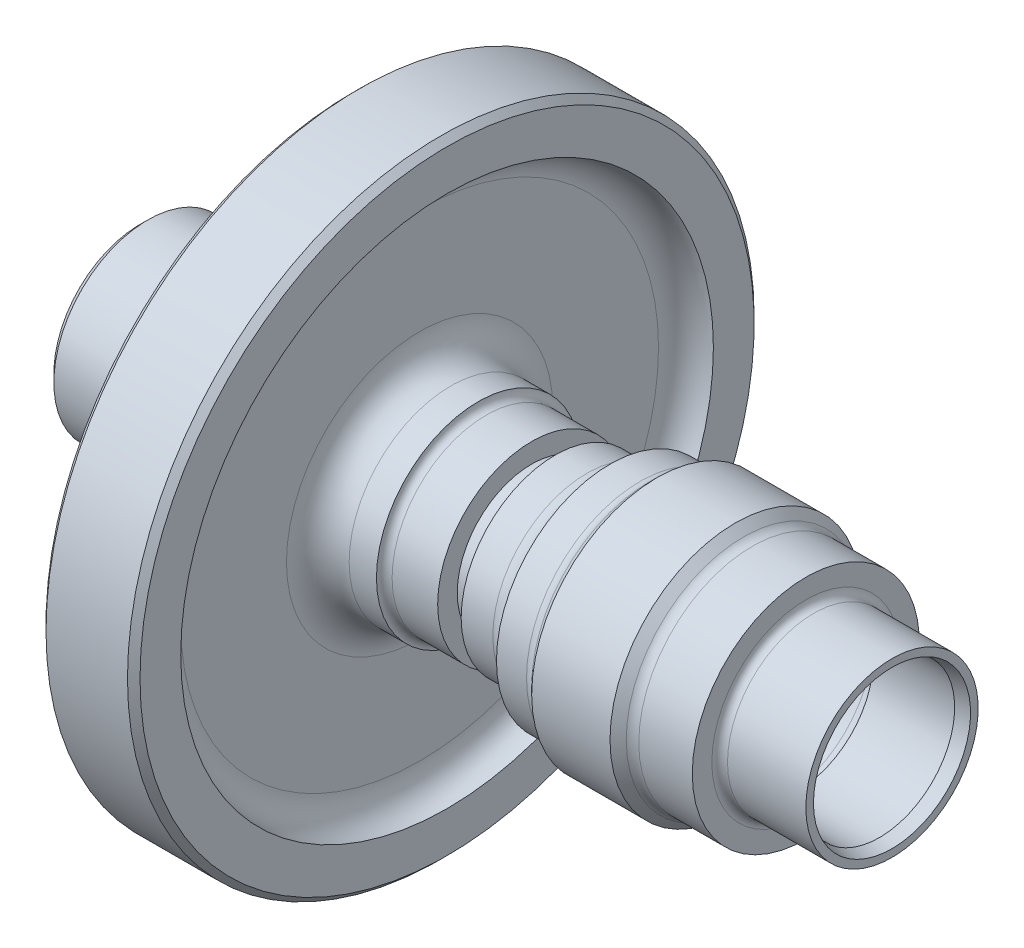
SolidWorks part; units mm, degrees
ref_plane "Front Plane" through (0, 0, 0) normal (0, 0, 1) x (1, 0, 0)
ref_plane "Top Plane" through (0, 0, 0) normal (0, 1, 0) x (1, 0, 0)
ref_plane "Right Plane" through (0, 0, 0) normal (1, 0, 0) x (0, 0, -1)
sketch "Sketch1" plane through (0, 0, 0) normal (0, 0, 1) x (1, 0, 0)
  line L0 (0, 0) -> (142.8155, 0) construction
  line L1 (0, 15.0812) -> (0, 17.4625)
  line L2 (0, 17.4625) -> (1.5875, 19.05)
  line L3 (1.5875, 19.05) -> (16.1925, 19.05)
  line L4 (17.78, 20.6375) -> (17.78, 25.4)
  line L5 (17.78, 25.4) -> (21.2785, 25.4)
  line L6 (26.041, 20.6375) -> (42.3926, 20.6375)
  line L7 (48.7426, 26.9875) -> (48.7426, 48.4124)
  line L8 (43.18, 53.975) -> (43.18, 62.23)
  line L9 (44.45, 63.5) -> (60.96, 63.5)
  line L10 (62.23, 62.23) -> (62.23, 53.975)
  line L11 (56.6674, 48.4124) -> (56.6674, 26.9875)
  line L12 (63.0174, 20.6375) -> (68.5536, 20.6375)
  line L13 (70.1411, 19.05) -> (79.375, 19.05)
  line L14 (79.375, 19.05) -> (79.375, 15.0812)
  line L15 (79.375, 15.0812) -> (84.1375, 15.0812)
  line L16 (84.1375, 15.0812) -> (84.1375, 19.05)
  line L17 (84.1375, 19.05) -> (90.5552, 19.05)
  line L18 (95.25, 23.0124) -> (101.3353, 23.0124)
  line L19 (103.1313, 23.7563) -> (104.775, 25.4)
  line L20 (104.775, 25.4) -> (120.65, 25.4)
  line L21 (120.65, 25.4) -> (122.2937, 23.7563)
  line L22 (124.0897, 23.0124) -> (134.9375, 23.0124)
  line L23 (134.9375, 23.0124) -> (134.9375, 19.05)
  line L24 (136.525, 17.4625) -> (152.4, 17.4625)
  line L25 (152.4, 17.4625) -> (152.4, 15.9206)
  line L26 (149.86, 15.24) -> (133.35, 15.24)
  line L27 (129.54, 19.05) -> (106.68, 19.05)
  line L28 (101.6, 13.97) -> (101.6, 11.9062)
  line L29 (101.6, 11.9062) -> (26.67, 11.9062)
  line L30 (25.4, 13.1762) -> (25.4, 15.0813)
  line L31 (23.8188, 16.6624) -> (14.1675, 16.6624)
  line L32 (26.67, 11.9062) -> (25.4, 13.1762)
  line L33 (11.1125, 16.0569) -> (11.1125, 15.875)
  line L34 (149.86, 15.24) -> (152.4, 15.9206)
  line L35 (60.96, 63.5) -> (62.23, 62.23)
  line L36 (43.18, 62.23) -> (44.45, 63.5)
  line L38 (11.1125, 15.875) -> (2.9623, 15.875)
  line L39 (1.5875, 15.0812) -> (0, 15.0812)
  arc A0 (16.1925, 19.05) -> (17.78, 20.6375) centre (16.1925, 20.6375) ccw
  arc A1 (21.2785, 25.4) -> (26.041, 20.6375) centre (26.041, 25.4) ccw
  arc A2 (42.3926, 20.6375) -> (48.7426, 26.9875) centre (42.3926, 26.9875) ccw
  arc A3 (48.7426, 48.4124) -> (43.18, 53.975) centre (43.18, 48.4124) ccw
  arc A4 (62.23, 53.975) -> (56.6674, 48.4124) centre (62.23, 48.4124) ccw
  arc A5 (56.6674, 26.9875) -> (63.0174, 20.6375) centre (63.0174, 26.9875) ccw
  arc A6 (68.5536, 20.6375) -> (70.1411, 19.05) centre (70.1411, 20.6375) ccw
  arc A7 (90.5552, 19.05) -> (95.25, 23.0124) centre (90.5552, 23.8125) ccw
  arc A8 (134.9375, 19.05) -> (136.525, 17.4625) centre (136.525, 19.05) ccw
  arc A9 (133.35, 15.24) -> (129.54, 19.05) centre (129.54, 15.24) ccw
  arc A10 (106.68, 19.05) -> (101.6, 13.97) centre (106.68, 13.97) ccw
  arc A11 (25.4, 15.0813) -> (23.8188, 16.6624) centre (23.8188, 15.0813) ccw
  arc A12 (2.9623, 15.875) -> (1.5875, 15.0812) centre (2.9623, 14.2875) ccw
  arc A13 (14.1675, 16.6624) -> (11.1125, 16.0569) centre (12.7, 16.0569) ccw
  arc A14 (101.3353, 23.0124) -> (103.1313, 23.7563) centre (101.3353, 25.5524) ccw
  arc A15 (124.0897, 23.0124) -> (122.2937, 23.7563) centre (124.0897, 25.5524) cw
  point P19 (62.23, 63.5)
  point P20 (43.18, 63.5)
  point P53 (25.4, 11.9062)
  dimension "D1" = 1.5875
  dimension "D2" = 17.6444
  dimension "D6" = 1.5875
  dimension "D12" = 12.7
  dimension "D18" = 3.81
  dimension "D21" = 5.08
  dimension "D25" = 4.7625
  dimension "D29" = 1.5875
  dimension "D30" = 3.4985
  dimension "D31" = 6.35
  dimension "D32" = 6.35
  dimension "D33" = 5.5626
  dimension "D34" = 34.925
  dimension "D38" = 107.95
  dimension "D44" = 2.54
  dimension "D45" = 2.54
  dimension "D48" = 1.5875
  dimension "D3" = 38.1
  dimension "D4" = 45
  dimension "D5" = 1.5875
  dimension "D7" = 1.5875
  dimension "D8" = 30.1625
  dimension "D9" = 31.75
  dimension "D10" = 33.3248
  dimension "D11" = 25.4
  dimension "D13" = 23.8125
  dimension "D14" = 152.4
  dimension "D16" = 17.4625
  dimension "D17" = 19.05
  dimension "D19" = 38.1
  dimension "D20" = 50.8
  dimension "D22" = 31.75
  dimension "D23" = 15.875
  dimension "D24" = 46.0248
  dimension "D26" = 9.525
  dimension "D27" = 50.8
  dimension "D28" = 17.78
  dimension "D35" = 19.05
  dimension "D36" = 7.9248
  dimension "D37" = 25.4
  dimension "D39" = 30.1625
  dimension "D40" = 127
  dimension "D41" = 4.7625
  dimension "D46" = 38.1
  dimension "D47" = 50.8
  dimension "D49" = 15
  dimension "D50" = 2.54
sketch "Sketch2" plane through (0, 0, 0) normal (0, 0, 1) x (1, 0, 0)
  line L0 (-19.9256, 0) -> (168.6458, 0) construction
  line L1 (-6.35, 69.85) -> (158.75, 69.85)
  line L2 (-6.35, 69.85) -> (-6.35, 0)
  line L3 (-6.35, 0) -> (158.75, 0)
  line L4 (158.75, 69.85) -> (158.75, 0)
  line L5 (0, 15.0812) -> (0, 17.4625) construction
  line L6 (152.4, 17.4625) -> (152.4, 15.9206) construction
  dimension "D1" = 139.7
  dimension "D2" = 6.35
  dimension "D3" = 6.35
revolve "Stock" add sketch "Sketch2" angle 360 about L0
sketch "Sketch3" plane through (0, 0, 0) normal (0, 0, 1) x (1, 0, 0)
  line L0 (67.1974, 66.0709) -> (153.302, 66.0709)
  line L1 (154.572, 64.8009) -> (154.572, 0)
  line L2 (158.75, -69.85) -> (158.75, 69.85) construction
  line L3 (158.75, 69.85) -> (-6.35, 69.85) construction
  line L4 (158.75, 0) -> (158.75, 69.85)
  line L5 (158.75, 69.85) -> (66.3084, 69.85)
  line L6 (66.3084, 66.9599) -> (66.3084, 69.85)
  line L7 (154.572, 0) -> (158.75, 0)
  line L8 (-15.1072, 0) -> (164.7172, 0) construction
  line L9 (153.302, 66.0709) -> (154.572, 64.8009)
  arc A0 (67.1974, 66.0709) -> (66.3084, 66.9599) centre (67.1974, 66.9599) cw
  point P1 (154.572, 66.0709)
  dimension "D1" = 0.889
revolve "Cut-Revolve1" cut sketch "Sketch3" angle 360 about L8
sketch "Sketch4" plane through (0, 0, 0) normal (0, 0, 1) x (1, 0, 0)
  line L0 (44.45, 63.5) -> (60.96, 63.5) construction
  line L1 (43.18, 62.23) -> (44.45, 63.5) construction
  line L2 (43.18, 53.975) -> (43.18, 62.23) construction
  line L3 (48.7426, 26.9875) -> (48.7426, 48.4124) construction
  line L4 (26.041, 20.6375) -> (42.3926, 20.6375) construction
  line L5 (17.78, 25.4) -> (21.2785, 25.4) construction
  line L6 (17.78, 20.6375) -> (17.78, 25.4) construction
  line L7 (1.5875, 19.05) -> (16.1925, 19.05) construction
  line L8 (0, 17.4625) -> (1.5875, 19.05) construction
  line L9 (0, 15.0812) -> (0, 17.4625) construction
  line L10 (1.5875, 15.0812) -> (0, 15.0812) construction
  line L11 (11.1125, 15.875) -> (2.9623, 15.875) construction
  line L12 (23.8188, 16.6624) -> (14.1675, 16.6624) construction
  line L13 (25.4, 13.1762) -> (25.4, 15.0813) construction
  line L14 (26.67, 11.9062) -> (25.4, 13.1762) construction
  line L15 (101.6, 11.9062) -> (26.67, 11.9062) construction
  line L16 (44.45, 63.5) -> (69.5582, 63.5)
  line L17 (43.18, 62.23) -> (44.45, 63.5)
  line L18 (43.18, 53.975) -> (43.18, 62.23)
  line L19 (48.7426, 26.9875) -> (48.7426, 48.4124)
  line L20 (26.041, 20.6375) -> (42.3926, 20.6375)
  line L21 (17.78, 25.4) -> (21.2785, 25.4)
  line L22 (17.78, 20.6375) -> (17.78, 25.4)
  line L23 (1.5875, 19.05) -> (16.1925, 19.05)
  line L24 (0, 17.4625) -> (1.5875, 19.05)
  line L25 (0, 15.0812) -> (0, 17.4625)
  line L26 (1.5875, 15.0812) -> (0, 15.0812)
  line L27 (11.1125, 15.875) -> (2.9623, 15.875)
  line L28 (23.8188, 16.6624) -> (14.1675, 16.6624)
  line L29 (25.4, 13.1762) -> (25.4, 15.0813)
  line L30 (26.67, 11.9062) -> (25.4, 13.1762)
  line L31 (107.95, 11.9063) -> (26.67, 11.9062)
  line L32 (70.4472, 66.0709) -> (70.4472, 64.389)
  line L33 (153.302, 66.0709) -> (67.1974, 66.0709) construction
  line L34 (107.95, 11.9063) -> (115.104, 0)
  line L35 (0, 0) -> (142.8155, 0) construction
  line L36 (-6.35, 69.85) -> (-6.35, -69.85) construction
  line L38 (66.3084, 69.85) -> (-6.35, 69.85) construction
  line L39 (-6.35, 69.85) -> (-6.35, 0)
  line L40 (11.1125, 15.875) -> (11.1125, 16.0569)
  line L41 (66.3084, 69.85) -> (-6.35, 69.85)
  line L42 (70.4472, 66.0709) -> (67.1974, 66.0709)
  line L43 (171.8406, 0) -> (-23.4157, 0) construction
  line L44 (66.3084, 66.9599) -> (66.3084, 69.85)
  line L45 (154.572, -64.8009) -> (154.572, 64.8009) construction
  line L46 (-6.35, 0) -> (115.104, 0)
  arc A0 (48.7426, 48.4124) -> (43.18, 53.975) centre (43.18, 48.4124) ccw construction
  arc A1 (42.3926, 20.6375) -> (48.7426, 26.9875) centre (42.3926, 26.9875) ccw construction
  arc A2 (21.2785, 25.4) -> (26.041, 20.6375) centre (26.041, 25.4) ccw construction
  arc A3 (16.1925, 19.05) -> (17.78, 20.6375) centre (16.1925, 20.6375) ccw construction
  arc A4 (2.9623, 15.875) -> (1.5875, 15.0812) centre (2.9623, 14.2875) ccw construction
  arc A5 (14.1675, 16.6624) -> (11.1125, 16.0569) centre (12.7, 16.0569) ccw construction
  arc A6 (25.4, 15.0813) -> (23.8188, 16.6624) centre (23.8188, 15.0813) ccw construction
  arc A7 (48.7426, 48.4124) -> (43.18, 53.975) centre (43.18, 48.4124) ccw
  arc A8 (42.3926, 20.6375) -> (48.7426, 26.9875) centre (42.3926, 26.9875) ccw
  arc A9 (21.2785, 25.4) -> (26.041, 20.6375) centre (26.041, 25.4) ccw
  arc A10 (16.1925, 19.05) -> (17.78, 20.6375) centre (16.1925, 20.6375) ccw
  arc A11 (2.9623, 15.875) -> (1.5875, 15.0812) centre (2.9623, 14.2875) ccw
  arc A12 (14.1675, 16.6624) -> (11.1125, 16.0569) centre (12.7, 16.0569) ccw
  arc A13 (25.4, 15.0813) -> (23.8188, 16.6624) centre (23.8188, 15.0813) ccw
  arc A14 (69.5582, 63.5) -> (70.4472, 64.389) centre (69.5582, 64.389) ccw
  arc A15 (66.3084, 66.9599) -> (67.1974, 66.0709) centre (67.1974, 66.9599) ccw construction
  arc A16 (66.3084, 66.9599) -> (67.1974, 66.0709) centre (67.1974, 66.9599) ccw
  dimension "D1" = 0.889
  dimension "D2" = 59
  dimension "D3" = 107.95
  dimension "D4" = 84.1248
revolve "Cut-Revolve3" cut sketch "Sketch4" angle 360 about L43
sketch "Sketch5" plane through (0, 0, 0) normal (0, 0, 1) x (1, 0, 0)
  line L1 (101.6, 13.97) -> (101.6, 11.9062) construction
  line L2 (129.54, 19.05) -> (106.68, 19.05) construction
  line L3 (149.86, 15.24) -> (133.35, 15.24) construction
  line L4 (149.86, 15.24) -> (152.4, 15.9206) construction
  line L5 (152.4, 17.4625) -> (152.4, 15.9206) construction
  line L6 (136.525, 17.4625) -> (152.4, 17.4625) construction
  line L7 (134.9375, 23.0124) -> (134.9375, 19.05) construction
  line L8 (124.0897, 23.0124) -> (134.9375, 23.0124) construction
  line L9 (120.65, 25.4) -> (122.2937, 23.7563) construction
  line L10 (104.775, 25.4) -> (120.65, 25.4) construction
  line L11 (103.1313, 23.7563) -> (104.775, 25.4) construction
  line L12 (95.25, 23.0124) -> (101.3353, 23.0124) construction
  line L13 (84.1375, 19.05) -> (90.5552, 19.05) construction
  line L14 (84.1375, 15.0812) -> (84.1375, 19.05) construction
  line L15 (79.375, 15.0812) -> (84.1375, 15.0812) construction
  line L16 (79.375, 19.05) -> (79.375, 15.0812) construction
  line L17 (70.1411, 19.05) -> (79.375, 19.05) construction
  line L18 (63.0174, 20.6375) -> (68.5536, 20.6375) construction
  line L19 (56.6674, 48.4124) -> (56.6674, 26.9875) construction
  line L20 (62.23, 62.23) -> (62.23, 53.975) construction
  line L21 (60.96, 63.5) -> (62.23, 62.23) construction
  line L22 (154.572, -64.8009) -> (154.572, 64.8009) construction
  line L23 (101.6, 13.97) -> (101.6, 11.9062)
  line L24 (129.54, 19.05) -> (106.68, 19.05)
  line L25 (149.86, 15.24) -> (133.35, 15.24)
  line L26 (149.86, 15.24) -> (152.4, 15.9206)
  line L27 (152.4, 17.4625) -> (152.4, 15.9206)
  line L28 (136.525, 17.4625) -> (152.4, 17.4625)
  line L29 (134.9375, 23.0124) -> (134.9375, 19.05)
  line L30 (124.0897, 23.0124) -> (134.9375, 23.0124)
  line L31 (120.65, 25.4) -> (122.2937, 23.7563)
  line L32 (104.775, 25.4) -> (120.65, 25.4)
  line L33 (103.1313, 23.7563) -> (104.775, 25.4)
  line L34 (95.25, 23.0124) -> (101.3353, 23.0124)
  line L35 (84.1375, 19.05) -> (90.5552, 19.05)
  line L36 (84.1375, 15.0812) -> (84.1375, 19.05)
  line L37 (79.375, 15.0812) -> (84.1375, 15.0812)
  line L38 (79.375, 19.05) -> (79.375, 15.0812)
  line L39 (70.1411, 19.05) -> (79.375, 19.05)
  line L40 (63.0174, 20.6375) -> (68.5536, 20.6375)
  line L41 (56.6674, 48.4124) -> (56.6674, 26.9875)
  line L42 (62.23, 62.23) -> (62.23, 53.975)
  line L43 (60.96, 63.5) -> (62.23, 62.23)
  line L44 (70.4472, 66.0709) -> (70.4472, -66.0709) construction
  line L45 (153.302, 66.0709) -> (70.4472, 66.0709) construction
  line L46 (69.5582, 63.5) -> (44.45, 63.5) construction
  line L47 (154.572, 0) -> (154.572, 64.8009)
  line L48 (70.4472, 66.0709) -> (70.4472, 64.389)
  line L49 (153.302, 66.0709) -> (70.4472, 66.0709)
  line L50 (69.5582, 63.5) -> (60.96, 63.5)
  line L51 (-11.8138, 0) -> (163.7809, 0) construction
  line L52 (154.572, 64.8009) -> (153.302, 66.0709) construction
  line L53 (154.572, 64.8009) -> (153.302, 66.0709)
  line L54 (115.104, 0) -> (107.95, 11.9062) construction
  line L55 (107.95, 11.9062) -> (26.67, 11.9062) construction
  line L56 (115.104, 0) -> (107.95, 11.9062)
  line L57 (107.95, 11.9062) -> (101.6, 11.9062)
  line L59 (115.104, 0) -> (154.572, 0)
  arc A0 (106.68, 19.05) -> (101.6, 13.97) centre (106.68, 13.97) ccw construction
  arc A1 (133.35, 15.24) -> (129.54, 19.05) centre (129.54, 15.24) ccw construction
  arc A2 (134.9375, 19.05) -> (136.525, 17.4625) centre (136.525, 19.05) ccw construction
  arc A3 (122.2937, 23.7563) -> (124.0897, 23.0124) centre (124.0897, 25.5524) ccw construction
  arc A4 (101.3353, 23.0124) -> (103.1313, 23.7563) centre (101.3353, 25.5524) ccw construction
  arc A5 (90.5552, 19.05) -> (95.25, 23.0124) centre (90.5552, 23.8125) ccw construction
  arc A6 (68.5536, 20.6375) -> (70.1411, 19.05) centre (70.1411, 20.6375) ccw construction
  arc A7 (56.6674, 26.9875) -> (63.0174, 20.6375) centre (63.0174, 26.9875) ccw construction
  arc A8 (62.23, 53.975) -> (56.6674, 48.4124) centre (62.23, 48.4124) ccw construction
  arc A9 (106.68, 19.05) -> (101.6, 13.97) centre (106.68, 13.97) ccw
  arc A10 (133.35, 15.24) -> (129.54, 19.05) centre (129.54, 15.24) ccw
  arc A11 (134.9375, 19.05) -> (136.525, 17.4625) centre (136.525, 19.05) ccw
  arc A12 (122.2937, 23.7563) -> (124.0897, 23.0124) centre (124.0897, 25.5524) ccw
  arc A13 (101.3353, 23.0124) -> (103.1313, 23.7563) centre (101.3353, 25.5524) ccw
  arc A14 (90.5552, 19.05) -> (95.25, 23.0124) centre (90.5552, 23.8125) ccw
  arc A15 (68.5536, 20.6375) -> (70.1411, 19.05) centre (70.1411, 20.6375) ccw
  arc A16 (56.6674, 26.9875) -> (63.0174, 20.6375) centre (63.0174, 26.9875) ccw
  arc A17 (62.23, 53.975) -> (56.6674, 48.4124) centre (62.23, 48.4124) ccw
  arc A18 (69.5582, 63.5) -> (70.4472, 64.389) centre (69.5582, 64.389) ccw construction
  arc A19 (69.5582, 63.5) -> (70.4472, 64.389) centre (69.5582, 64.389) ccw
revolve "Cut-Revolve4" cut sketch "Sketch5" angle 360 about L51
